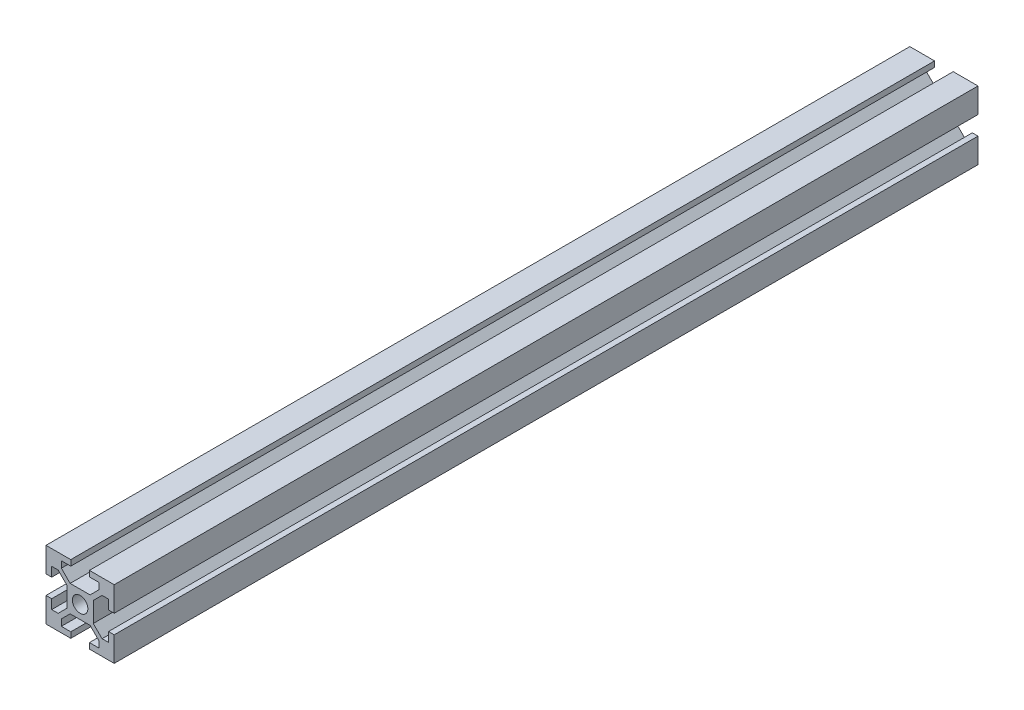
SolidWorks part; units mm, degrees
ref_plane "前视基准面" through (0, 0, 0) normal (0, 0, 1) x (1, 0, 0)
ref_plane "上视基准面" through (0, 0, 0) normal (0, 1, 0) x (1, 0, 0)
ref_plane "右视基准面" through (0, 0, 0) normal (1, 0, 0) x (0, 0, -1)
sketch "草图1" plane through (0, 0, 0) normal (0, 0, 1) x (1, 0, 0)
  line L0 (-4.1, 15) -> (-4.1, 12.5)
  line L1 (-4.3858, -5.8) -> (4.3858, -5.8)
  line L2 (-5.8, -4.3858) -> (-5.8, 4.3858)
  line L3 (-4.3858, 5.8) -> (4.3858, 5.8)
  line L4 (5.8, -4.3858) -> (5.8, 4.3858)
  line L5 (-9.6642, 8.25) -> (-12.5, 8.25)
  line L6 (-8.25, -12.5) -> (-4.1, -12.5)
  line L7 (-15, -15) -> (-4.1, -15)
  line L8 (-15, -15) -> (-15, -4.1)
  line L9 (-8.25, 15) -> (-4.1, 15)
  line L10 (15, -15) -> (15, -4.1)
  line L11 (-8.25, 9.6642) -> (-8.25, 12.5)
  line L12 (-8.25, 15) -> (-15, 15)
  line L13 (9.6642, 8.25) -> (12.5, 8.25)
  line L14 (8.25, 9.6642) -> (8.25, 12.5)
  line L15 (8.25, 15) -> (15, 15)
  line L16 (15, 8.25) -> (15, 15)
  line L17 (9.6642, -8.25) -> (12.5, -8.25)
  line L18 (8.25, -9.6642) -> (8.25, -12.5)
  line L19 (8.25, -15) -> (15, -15)
  line L20 (15, -8.25) -> (15, -15)
  line L21 (-15, 8.25) -> (-15, 15)
  line L22 (-9.6642, -8.25) -> (-12.5, -8.25)
  line L23 (-8.25, -9.6642) -> (-8.25, -12.5)
  line L24 (-8.25, -15) -> (-15, -15)
  line L25 (-15, -8.25) -> (-15, -15)
  line L26 (-12.5, -8.25) -> (-12.5, -4.1)
  line L27 (-8.25, 12.5) -> (-4.1, 12.5)
  line L28 (12.5, -8.25) -> (12.5, -4.1)
  line L29 (-8.25, 9.6642) -> (-4.3858, 5.8)
  line L30 (-9.6642, 8.25) -> (-5.8, 4.3858)
  line L31 (8.25, 9.6642) -> (4.3858, 5.8)
  line L32 (9.6642, 8.25) -> (5.8, 4.3858)
  line L33 (4.3858, -5.8) -> (8.25, -9.6642)
  line L34 (-5.8, -4.3858) -> (-9.6642, -8.25)
  line L35 (4.1, 15) -> (4.1, 12.5)
  line L36 (5.8, -4.3858) -> (9.6642, -8.25)
  line L37 (-4.3858, -5.8) -> (-8.25, -9.6642)
  line L38 (4.1, 15) -> (15, 15)
  line L39 (4.1, 12.5) -> (8.25, 12.5)
  line L40 (-4.1, -12.5) -> (-4.1, -15)
  line L41 (4.1, -15) -> (15, -15)
  line L42 (4.1, -12.5) -> (8.25, -12.5)
  line L43 (4.1, -12.5) -> (4.1, -15)
  line L44 (-15, 4.1) -> (-12.5, 4.1)
  line L45 (-15, -4.1) -> (-12.5, -4.1)
  line L46 (-15, 4.1) -> (-15, 15)
  line L47 (-12.5, 4.1) -> (-12.5, 8.25)
  line L48 (12.5, -4.1) -> (15, -4.1)
  line L49 (12.5, 4.1) -> (15, 4.1)
  line L50 (12.5, 4.1) -> (12.5, 8.25)
  line L51 (15, 4.1) -> (15, 15)
  line L52 (-15, 8.25) -> (-15, 4.1)
  line L53 (15, 8.25) -> (15, 4.1)
  line L54 (8.25, -15) -> (4.1, -15)
  line L55 (8.25, 15) -> (4.1, 15)
  circle A0 centre (0, 0) radius 3.4
extrude "凸台-拉伸1" add sketch "草图1" along normal blind 380 contours L49 L51 L16 L15 L38 L35 L39 L14 L31 L3 L29 L11 L27 L0 L9 L12 L21 L46 L44 L47 L5 L30 L2 L34 L22 L26 L45 L8 L7 L40 L6 L23 L37 L1 L33 L18 L42 L43 L41 L19 L10 L48 L28 L17 L36 L4 L32 L13
